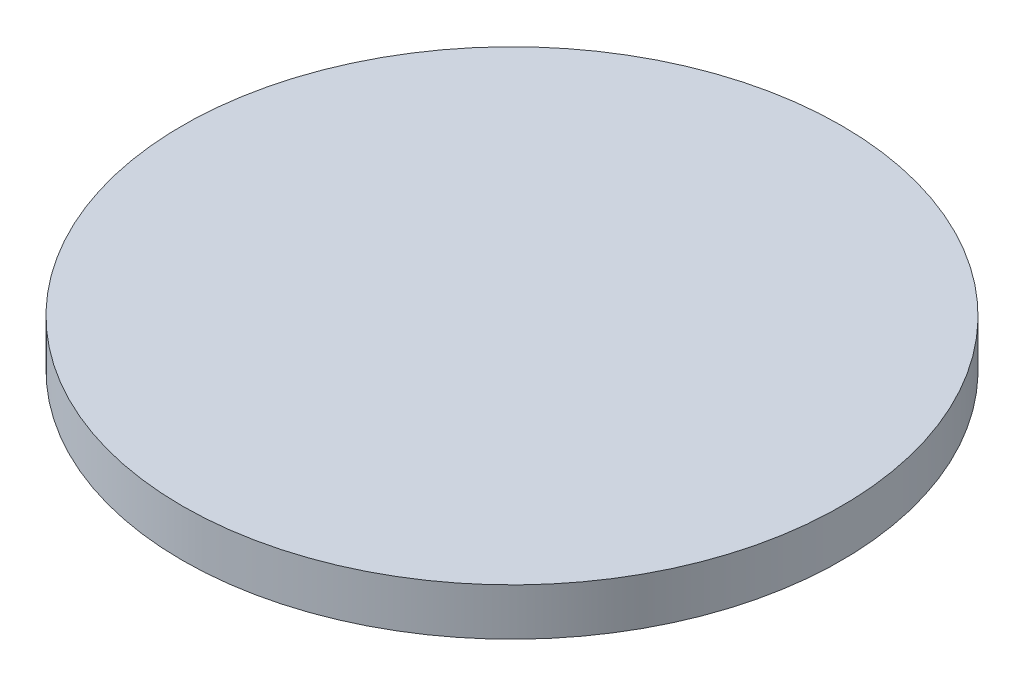
SolidWorks part; units mm, degrees
ref_plane "Front" through (0, 0, 0) normal (0, 0, 1) x (1, 0, 0)
ref_plane "Top" through (0, 0, 0) normal (0, 1, 0) x (1, 0, 0)
ref_plane "Right" through (0, 0, 0) normal (1, 0, 0) x (0, 0, -1)
sketch "Sketch1" plane through (0, 0, 0) normal (0, 1, 0) x (1, 0, 0)
  circle A0 centre (0, 0) radius 44.45
  dimension "D1" = 88.9
extrude "Boss-Extrude1" add sketch "Sketch1" along normal blind 6.35
